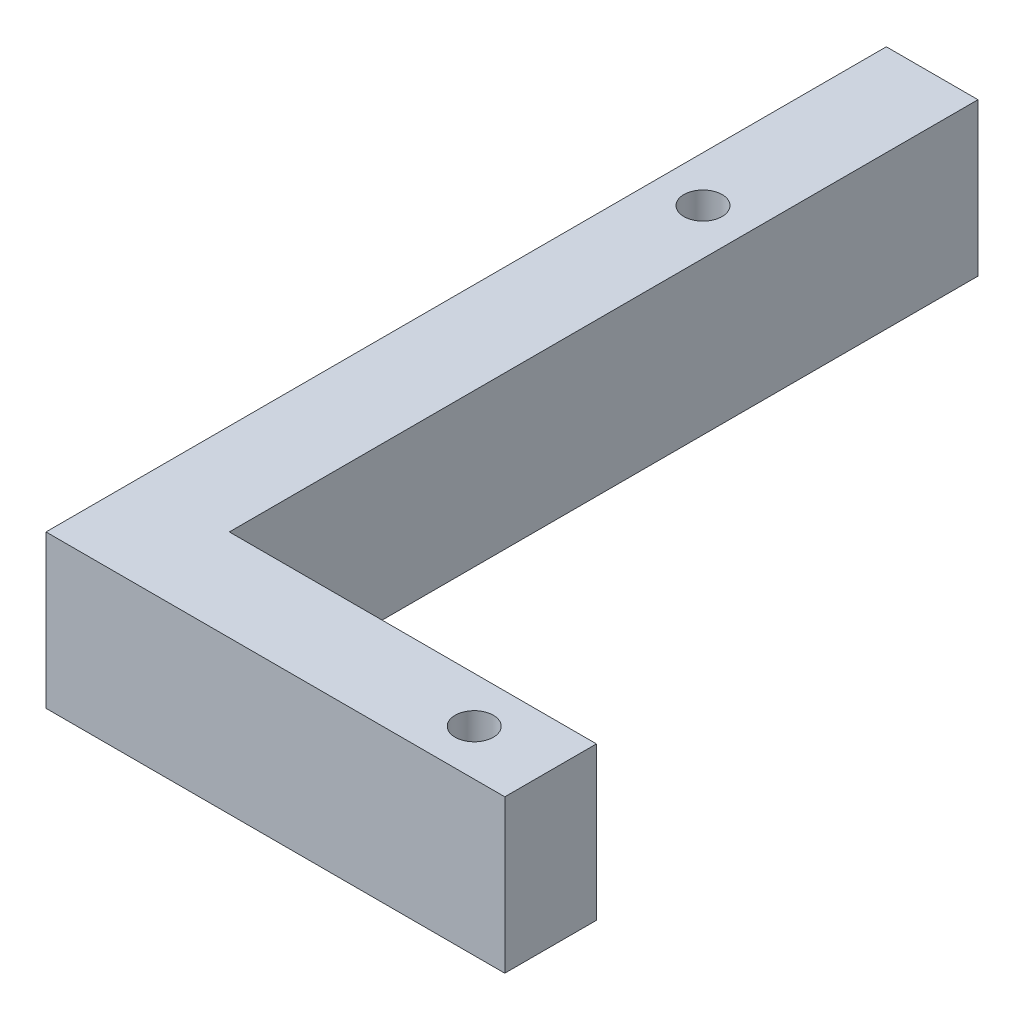
SolidWorks part; units mm, degrees
ref_plane "Front" through (0, 0, 0) normal (0, 0, 1) x (1, 0, 0)
ref_plane "Top" through (0, 0, 0) normal (0, 1, 0) x (1, 0, 0)
ref_plane "Right" through (0, 0, 0) normal (1, 0, 0) x (0, 0, -1)
sketch "Sketch1" plane through (0, 0, 0) normal (0, 1, 0) x (1, 0, 0)
  line L0 (3, 55) -> (3, 40)
  line L1 (0, 0) -> (6, 0)
  line L2 (0, 0) -> (0, 55)
  line L3 (0, 55) -> (6, 55)
  line L4 (6, 0) -> (6, 55)
  line L5 (6, 0) -> (30.028, 0)
  line L6 (6, 0) -> (6, 6)
  line L7 (6, 6) -> (30.028, 6)
  line L8 (30.028, 0) -> (30.028, 6)
  line L9 (30.028, 3) -> (25.028, 3)
  circle A0 centre (3, 40) radius 1.25
  circle A1 centre (25.028, 3) radius 1.25
  dimension "D1" = 6
  dimension "D2" = 40
  dimension "D3" = 6
  dimension "D4" = 15
  dimension "D5" = 5
extrude "Boss-Extrude1" add sketch "Sketch1" along normal blind 10
